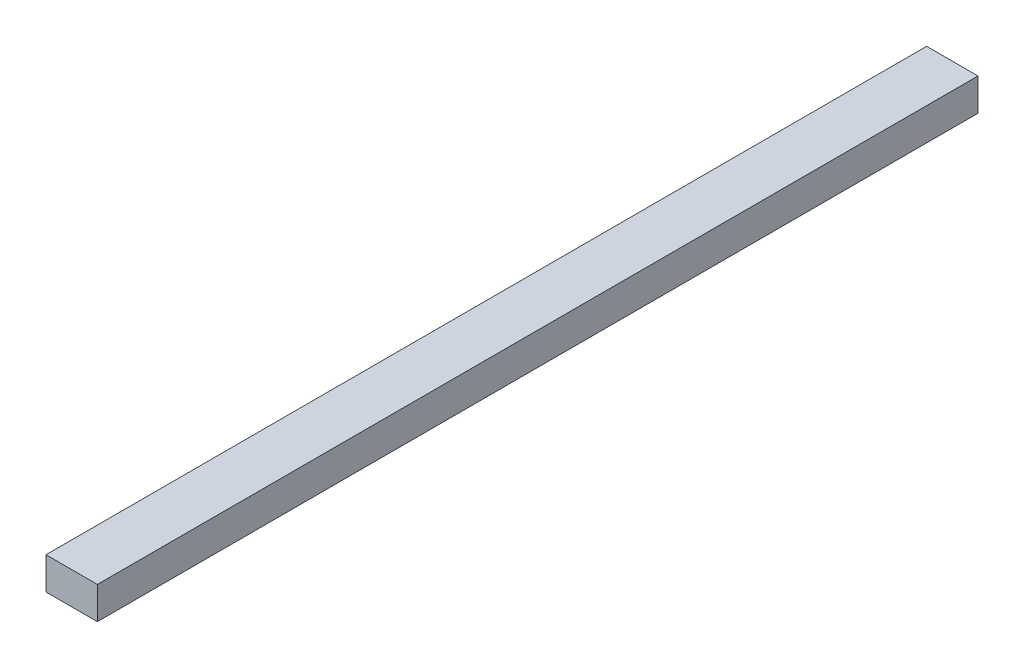
SolidWorks part; units mm, degrees
ref_plane "Front Plane" through (0, 0, 0) normal (0, 0, 1) x (1, 0, 0)
ref_plane "Top Plane" through (0, 0, 0) normal (0, 1, 0) x (1, 0, 0)
ref_plane "Right Plane" through (0, 0, 0) normal (1, 0, 0) x (0, 0, -1)
sketch "Sketch1" plane through (0, 0, 0) normal (0, 0, 1) x (1, 0, 0)
  line L7 (-35, -22) -> (35, -22)
  line L8 (-35, -22) -> (-35, 22)
  line L9 (-35, 22) -> (35, 22)
  line L10 (35, -22) -> (35, 22)
  line L11 (-35, -22) -> (35, 22) construction
  line L12 (-35, 22) -> (35, -22) construction
  point P10 (0, 0)
  dimension "D1" = 70
  dimension "D2" = 44
extrude "Boss-Extrude1" add sketch "Sketch1" along normal mid plane 1200
